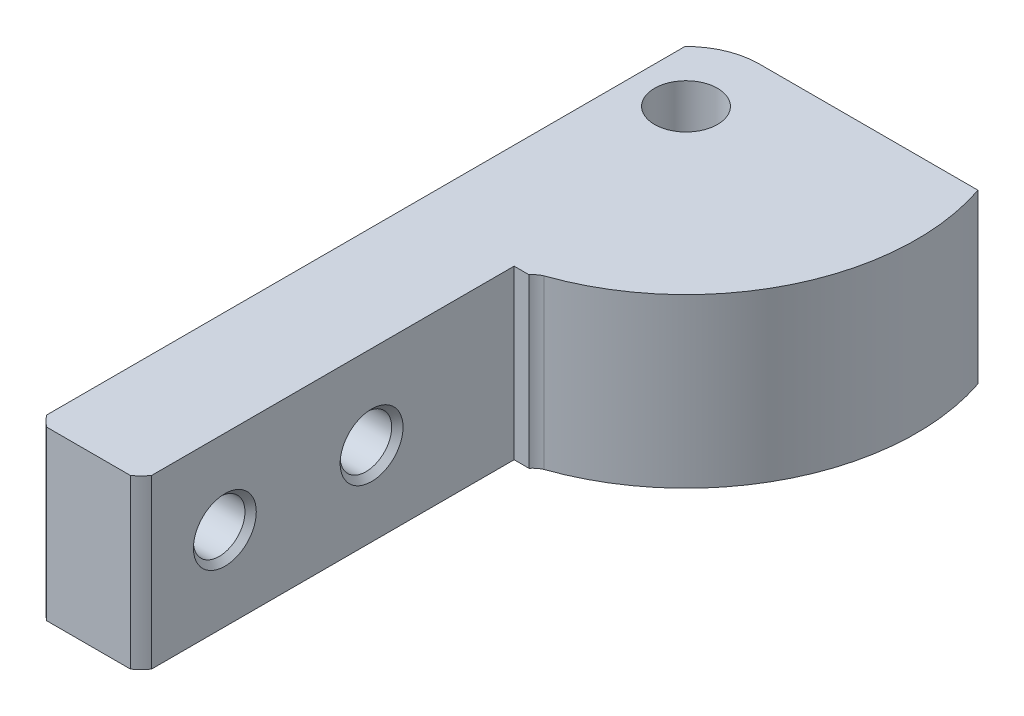
SolidWorks part; units mm, degrees
material "3.0205 (EN-AW 1200)"
ref_plane "前视基准面" through (0, 0, 0) normal (0, 0, 1) x (1, 0, 0)
ref_plane "上视基准面" through (0, 0, 0) normal (0, 1, 0) x (1, 0, 0)
ref_plane "右视基准面" through (0, 0, 0) normal (1, 0, 0) x (0, 0, -1)
ref_plane "基准面4" through (0, 4, 0) normal (0, 1, 0) x (1, 0, 0)
sketch "草图1" plane through (0, 4, 0) normal (0, 1, 0) x (1, 0, 0)
  line L0 (-2.5, 2.4495) -> (-2.5, -28)
  line L1 (-2, -28.5) -> (2, -28.5)
  line L2 (2.5, -28) -> (2.5, -10.7)
  line L3 (2.5, -10.7) -> (3.21, -10.7)
  line L4 (10.4283, 3.5) -> (0, 3.5)
  arc A0 (-2.5, -28) -> (-2, -28.5) centre (-0.5, -26.5) ccw
  arc A1 (2, -28.5) -> (2.5, -28) centre (0.5, -26.5) ccw
  arc A2 (3.21, -10.7) -> (3.6168, -10.3884) centre (4, -11.31) cw
  arc A3 (3.6168, -10.3884) -> (10.4283, 3.5) centre (0, 0) ccw
  arc A4 (0, 3.5) -> (-2.5, 2.4495) centre (0, 0) ccw
extrude "凸台-拉伸1" add sketch "草图1" against normal blind 8
hole_wizard "M2 间隙孔1" positions "草图3" profile "草图2" hole size "M2" standard "ANSI Metric"
sketch "草图3" plane through (-2.5, 0, 0) normal (-1, 0, 0) x (0, 0, 1)
  point P0 (17.5, 0)
sketch "草图2" plane through (-2.5, 0, 17.5) normal (0, 1, 0) x (0, 0, 1)
  line L0 (0, 0) -> (0, 13.5)
  line L1 (0, 13.5) -> (1.2295, 13.5)
  line L2 (1.2295, 13.5) -> (1.2295, 0)
  line L5 (1.2295, 0) -> (0, 0)
  line L11 (0, -6.35) -> (0, 107.95) construction
  dimension "通孔孔直径" = 2.459
  dimension "通孔孔深度" = 13.5
hole_wizard "M2 间隙孔2" positions "草图5" profile "草图4" hole size "M2" standard "ANSI Metric"
sketch "草图5" plane through (2.5, 0, 0) normal (1, 0, 0) x (0, 0, -1)
  point P0 (-24.5, 0)
sketch "草图4" plane through (2.5, 0, 24.5) normal (0, 1, 0) x (0, 0, -1)
  line L0 (0, 0) -> (0, 5)
  line L1 (0, 5) -> (1.2295, 5)
  line L2 (1.2295, 5) -> (1.2295, 0)
  line L5 (1.2295, 0) -> (0, 0)
  line L11 (0, -6.35) -> (0, 107.95) construction
  dimension "通孔孔直径" = 2.459
  dimension "通孔孔深度" = 5
hole_wizard "Ø3.0 (3) 直径孔1" positions "草图7" profile "草图6" hole size "Ø3.0" standard "ANSI Metric"
sketch "草图7" plane through (0, 4, 0) normal (0, 1, 0) x (1, 0, 0)
  point P0 (0, 0)
sketch "草图6" plane through (0, 4, 0) normal (1, 0, 0) x (0, 0, 1)
  line L0 (0, 0) -> (0, 8)
  line L1 (0, 8) -> (1.5, 8)
  line L2 (1.5, 8) -> (1.5, 0)
  line L5 (1.5, 0) -> (0, 0)
  line L11 (0, -6.35) -> (0, 107.95) construction
  dimension "通孔孔直径" = 3
  dimension "通孔孔深度" = 8
chamfer "倒角1" distance 0.2705 angle 45 4 edges at (2.5, 0, 16.2705) (-2.5, 0, 23.2705) (2.5, 0, 23.2705) (-2.5, 0, 18.7295)
